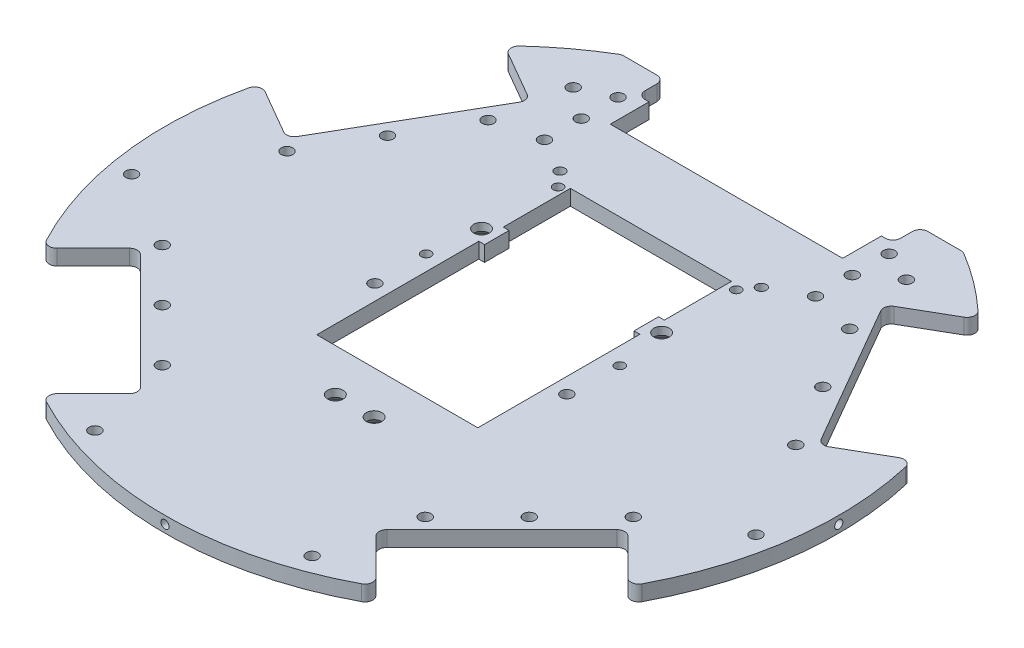
SolidWorks part; units mm, degrees
ref_plane "Front Plane" through (0, 0, 0) normal (0, 0, 1) x (1, 0, 0)
ref_plane "Top Plane" through (0, 0, 0) normal (0, 1, 0) x (1, 0, 0)
ref_plane "Right Plane" through (0, 0, 0) normal (1, 0, 0) x (0, 0, -1)
sketch "Sketch1" plane through (0, 0, 0) normal (0, 1, 0) x (1, 0, 0)
  line L0 (0, 75) -> (0, -70.0325) construction
  line L1 (0, 0) -> (57.1577, 33) construction
  line L2 (0, 0) -> (46.669, -46.669) construction
  line L3 (45.6577, 52.9186) -> (68.6577, 13.0814)
  line L4 (-44.0908, 75) -> (44.0908, 75) construction
  line L5 (62.9325, -30.4056) -> (30.4056, -62.9325)
  line L6 (45.6577, 52.9186) -> (61.1636, 61.8709)
  line L7 (68.6577, 13.0814) -> (84.1636, 22.0338)
  line L8 (30.4056, -62.9325) -> (43.0661, -75.593)
  line L9 (62.9325, -30.4056) -> (75.593, -43.0661)
  line L10 (-33, 69) -> (33, 69)
  line L11 (33, 69) -> (33, 75)
  line L12 (33, 75) -> (44.0908, 75)
  line L13 (0, 0) -> (-46.669, -46.669) construction
  line L14 (0, 0) -> (-57.1577, 33) construction
  line L15 (-33, 75) -> (-44.0908, 75)
  line L16 (-33, 69) -> (-33, 75)
  line L17 (-62.9325, -30.4056) -> (-75.593, -43.0661)
  line L18 (-30.4056, -62.9325) -> (-43.0661, -75.593)
  line L19 (-68.6577, 13.0814) -> (-84.1636, 22.0338)
  line L20 (-45.6577, 52.9186) -> (-61.1636, 61.8709)
  line L21 (-62.9325, -30.4056) -> (-30.4056, -62.9325)
  line L22 (-45.6577, 52.9186) -> (-68.6577, 13.0814)
  arc A0 (-43.0661, -75.593) -> (43.0661, -75.593) centre (0, 0) ccw
  arc A1 (61.1636, 61.8709) -> (44.0908, 75) centre (0, 0) ccw
  arc A2 (75.593, -43.0661) -> (84.1636, 22.0338) centre (0, 0) ccw
  arc A3 (-75.593, -43.0661) -> (-84.1636, 22.0338) centre (0, 0) cw
  arc A4 (-61.1636, 61.8709) -> (-44.0908, 75) centre (0, 0) cw
  point P27 (0, 69)
  dimension "D1" = 87
  dimension "D2" = 75
  dimension "D3" = 66
  dimension "D4" = 60
  dimension "D5" = 45
  dimension "D6" = 46
  dimension "D7" = 46
  dimension "D8" = 33
  dimension "D9" = 6
extrude "Boss-Extrude1" add sketch "Sketch1" along normal mid plane 4
fillet "Fillet1" radius 2 20 edges at (33, 0, -75) (-33, 0, -75) (44.0908, 0, -75) (68.6577, 0, -13.0814) (84.1636, 0, -22.0338) (45.6577, 0, -52.9186) (61.1636, 0, -61.8709) (62.9325, 0, 30.4056) (43.0661, 0, 75.593) (30.4056, 0, 62.9325) (75.593, 0, 43.0661) (-43.0661, 0, 75.593) (-30.4056, 0, 62.9325) (-75.593, 0, 43.0661) (-62.9325, 0, 30.4056) (-68.6577, 0, -13.0814) (-84.1636, 0, -22.0338) (-45.6577, 0, -52.9186) (-44.0908, 0, -75) (-61.1636, 0, -61.8709)
sketch "Sketch2" plane through (0, -2, 0) normal (0, -1, 0) x (-1, 0, 0)
  line L0 (46.6936, 43.1244) -> (65.6936, 10.2154) construction
  line L1 (60.8112, -26.8701) -> (33.9411, -53.7401) construction
  line L2 (46.6577, 51.1865) -> (67.6577, 14.8135) construction
  line L3 (61.5183, -31.8198) -> (31.8198, -61.5183) construction
  line L4 (70.3897, 14.0814) -> (81.8562, 20.7016) construction
  line L5 (73.7091, -41.1822) -> (64.3467, -31.8198) construction
  line L6 (35, 65) -> (35, 46) construction
  line L7 (26, 61) -> (26, 41) construction
  line L8 (35, 75) -> (43.5431, 75) construction
  line L9 (-33, 69) -> (33, 69) construction
  line L10 (-33, 69) -> (33, 69) construction
  line L11 (0, 69) -> (0, -87) construction
  line L12 (-26, 61) -> (-26, 41) construction
  line L13 (-35, 65) -> (-35, 46) construction
  line L14 (-60.8112, -26.8701) -> (-33.9411, -53.7401) construction
  line L15 (-46.6936, 43.1244) -> (-65.6936, 10.2154) construction
  arc A0 (-40.7037, -76.8909) -> (40.7037, -76.8909) centre (0, 0) ccw construction
  point P0 (46.6936, 43.1244)
  point P1 (56.1936, 26.6699)
  point P2 (65.6936, 10.2154)
  point P3 (60.8112, -26.8701)
  point P4 (47.3762, -40.3051)
  point P5 (33.9411, -53.7401)
  point P18 (35, 65)
  point P19 (35, 55.5)
  point P20 (35, 46)
  point P21 (26, 61)
  point P22 (26, 41)
  point P29 (0, 69)
  point P34 (0, 69)
  point P48 (-35, 55.5)
  point P49 (-47.3762, -40.3051)
  point P50 (-56.1936, 26.6699)
  dimension "D1" = 38
  dimension "D2" = 38
  dimension "D3" = 4
  dimension "D4" = 4
  dimension "D5" = 18
  dimension "D6" = 18
  dimension "D7" = 19
  dimension "D8" = 35
  dimension "10" = 10
  dimension "D9" = 20
  dimension "D10" = 8
  dimension "D11" = 26
hole_wizard "CSK for M3 SFHCS1" positions "3DSketch1" profile "Sketch3" countersink size "M3" standard "ANSI Metric"
sketch3d "3DSketch1"
  point P0 (46.6936, -2, -43.1244)
  point P3 (56.1936, -2, -26.6699)
  point P6 (65.6936, -2, -10.2154)
  point P9 (60.8112, -2, 26.8701)
  point P12 (47.3762, -2, 40.3051)
  point P15 (33.9411, -2, 53.7401)
  point P18 (-33.9411, -2, 53.7401)
  point P21 (-47.3762, -2, 40.3051)
  point P24 (-60.8112, -2, 26.8701)
  point P27 (-46.6936, -2, -43.1244)
  point P30 (-56.1936, -2, -26.6699)
  point P33 (-65.6936, -2, -10.2154)
  point P36 (-35, -2, -65)
  point P39 (-35, -2, -55.5)
  point P42 (-35, -2, -46)
  point P45 (35, -2, -46)
  point P48 (35, -2, -55.5)
  point P51 (35, -2, -65)
sketch "Sketch3" plane through (46.6936, -2, -43.1244) normal (1, 0, 0) x (0, 0, -1)
  line L0 (0, 0) -> (0, 10.4013)
  line L1 (0, 10.4013) -> (1.5, 9.5)
  line L2 (1.5, 9.5) -> (1.5, 1.3)
  line L3 (1.5, 1.3) -> (2.8, 0)
  line L5 (2.8, 0) -> (0, 0)
  line L6 (-1.5, 1.3) -> (-2.8, 0) construction
  line L10 (0, 10.4013) -> (-1.5, 9.5) construction
  line L11 (0, -6.35) -> (0, 107.95) construction
  dimension "Hole Dia." = 3
  dimension "Hole Depth" = 9.5
  dimension "Near C'Sink Dia." = 5.6
  dimension "Near C'Sink Angle" = 90
  dimension "Drill Angle" = 118
sketch "Sketch4" plane through (0, -2, 0) normal (0, -1, 0) x (1, 0, 0)
  line L0 (0, 0) -> (-43.0182, -61.4364) construction
  line L1 (0, 0) -> (-28.0457, 77.0548) construction
  line L2 (0, -69) -> (0, 87) construction
  line L3 (0, 0) -> (-80.6164, 15) construction
  line L4 (0, -69) -> (0, 87) construction
  line L5 (0, 0) -> (80.6164, 15) construction
  line L6 (0, 0) -> (28.0457, 77.0548) construction
  line L7 (0, 0) -> (43.0182, -61.4364) construction
  dimension "D1" = 75
  dimension "D2" = 35
  dimension "D3" = 82
  dimension "D4" = 20
  dimension "D5" = 82
  dimension "D6" = 15
hole_wizard "CSK for M3 SFHCS2" positions "3DSketch2" profile "Sketch5" countersink size "M3" standard "ANSI Metric"
sketch3d "3DSketch2"
  point P0 (43.0182, -2, -61.4364)
  point P3 (80.6164, -2, 15)
  point P6 (28.0457, -2, 77.0548)
  point P9 (-28.0457, -2, 77.0548)
  point P12 (-80.6164, -2, 15)
  point P15 (-43.0182, -2, -61.4364)
sketch "Sketch5" plane through (43.0182, -2, -61.4364) normal (1, 0, 0) x (0, 0, -1)
  line L0 (0, 0) -> (0, 10.4013)
  line L1 (0, 10.4013) -> (1.5, 9.5)
  line L2 (1.5, 9.5) -> (1.5, 1.3)
  line L3 (1.5, 1.3) -> (2.8, 0)
  line L5 (2.8, 0) -> (0, 0)
  line L6 (-1.5, 1.3) -> (-2.8, 0) construction
  line L10 (0, 10.4013) -> (-1.5, 9.5) construction
  line L11 (0, -6.35) -> (0, 107.95) construction
  dimension "Hole Dia." = 3
  dimension "Hole Depth" = 9.5
  dimension "Near C'Sink Dia." = 5.6
  dimension "Near C'Sink Angle" = 90
  dimension "Drill Angle" = 118
hole_wizard "CSK for M3 SFHCS3" positions "3DSketch3" profile "Sketch6" countersink size "M3" standard "ANSI Metric"
sketch3d "3DSketch3"
  point P0 (26, -2, -41)
  point P3 (26, -2, -61)
  point P6 (-26, -2, -41)
  point P9 (-26, -2, -61)
sketch "Sketch6" plane through (26, -2, -41) normal (1, 0, 0) x (0, 0, -1)
  line L0 (0, 0) -> (0, 10.2811)
  line L1 (0, 10.2811) -> (1.3, 9.5)
  line L2 (1.3, 9.5) -> (1.3, 1)
  line L3 (1.3, 1) -> (2.3, 0)
  line L5 (2.3, 0) -> (0, 0)
  line L6 (-1.3, 1) -> (-2.3, 0) construction
  line L10 (0, 10.2811) -> (-1.3, 9.5) construction
  line L11 (0, -6.35) -> (0, 107.95) construction
  dimension "Hole Dia." = 2.6
  dimension "Hole Depth" = 9.5
  dimension "Near C'Sink Dia." = 4.6
  dimension "Near C'Sink Angle" = 90
  dimension "Drill Angle" = 118
sketch "Sketch7" plane through (0, 0, 0) normal (0, 1, 0) x (1, 0, 0)
  arc A0 (-84.8058, 19.4159) -> (-76.8909, -40.7037) centre (0, 0) ccw construction
  arc A1 (76.8909, -40.7037) -> (84.8058, 19.4159) centre (0, 0) ccw construction
  arc A2 (-40.7037, -76.8909) -> (40.7037, -76.8909) centre (0, 0) ccw construction
  arc A3 (59.2176, 63.736) -> (44.5676, 74.7176) centre (0, 0) ccw construction
  arc A4 (-44.5676, 74.7176) -> (-59.2176, 63.736) centre (0, 0) ccw construction
  point P0 (-86.2557, -11.3558)
  point P1 (86.2557, -11.3558)
  point P5 (0, -87)
  point P9 (52.1823, 69.6133)
  point P13 (-52.1823, 69.6133)
ref_plane "Plane1" through (87, 0, 0) normal (1, 0, 0) x (0, 0, -1)
sketch "Sketch9" plane through (87, 0, 0) normal (1, 0, 0) x (0, 0, -1)
  circle A0 centre (0, 0) radius 1.05
  dimension "D1" = 2.1
ref_plane "Plane2" through (0, 0, 87) normal (0, 0, 1) x (1, 0, 0)
sketch "Sketch10" plane through (0, 0, 87) normal (0, 0, 1) x (1, 0, 0)
  circle A0 centre (0, 0) radius 1.05
  dimension "D1" = 2.1
ref_plane "Plane3" through (52.1823, 0, -69.6133) normal (0.5998, 0, -0.8002) x (-0.8002, 0, -0.5998)
sketch "Sketch11" plane through (52.1823, 0, -69.6133) normal (0.5998, 0, -0.8002) x (-0.8002, 0, -0.5998)
  circle A0 centre (0, 0) radius 1.05
  dimension "D1" = 2.1
sketch "Sketch12" plane through (0, 2, 0) normal (0, 1, 0) x (1, 0, 0)
  line L0 (-23.25, 18) -> (23.25, 18) construction
  line L1 (24.78, -8) -> (-24.78, -8) construction
  line L2 (-5, -38) -> (5, -38) construction
  line L3 (33, 69) -> (-33, 69) construction
  line L4 (-35, 75) -> (-43.5431, 75) construction
  point P0 (-23.25, 18)
  point P1 (23.25, 18)
  point P2 (-5, -38)
  point P3 (5, -38)
  point P4 (-24.78, -8)
  point P5 (24.78, -8)
  point P14 (0, 18)
  point P16 (0, -8)
  point P17 (0, -38)
  dimension "D1" = 51
  dimension "D2" = 83
  dimension "D3" = 56
  dimension "D4" = 49.56
  dimension "D5" = 10
  dimension "D6" = 46.5
sketch "Sketch14" plane through (0, -2, 0) normal (0, -1, 0) x (1, 0, 0)
  point P0 (23.25, -18)
  point P1 (-23.25, -18)
  point P3 (-24.78, 8)
  point P5 (24.78, 8)
  point P7 (5, 38)
  point P9 (-5, 38)
hole_wizard "CSK for M4 SFHCS3" positions "3DSketch7" profile "Sketch16" countersink size "M4" standard "ANSI Metric"
sketch3d "3DSketch7"
  point P0 (23.25, -2, -18)
  point P3 (-23.25, -2, -18)
  point P6 (-5, -2, 38)
  point P9 (5, -2, 38)
sketch "Sketch16" plane through (23.25, -2, -18) normal (1, 0, 0) x (0, 0, -1)
  line L0 (0, 0) -> (0, 10.7017)
  line L1 (0, 10.7017) -> (2, 9.5)
  line L2 (2, 9.5) -> (2, 2)
  line L3 (2, 2) -> (4, 0)
  line L5 (4, 0) -> (0, 0)
  line L6 (-2, 2) -> (-4, 0) construction
  line L10 (0, 10.7017) -> (-2, 9.5) construction
  line L11 (0, -6.35) -> (0, 107.95) construction
  dimension "Hole Dia." = 4
  dimension "Hole Depth" = 9.5
  dimension "Near C'Sink Dia." = 8
  dimension "Near C'Sink Angle" = 90
  dimension "Drill Angle" = 118
hole_wizard "CSK for M3 SFHCS4" positions "3DSketch8" profile "Sketch17" countersink size "M3" standard "ANSI Metric"
sketch3d "3DSketch8"
  point P0 (24.78, -2, 8)
  point P3 (-24.78, -2, 8)
sketch "Sketch17" plane through (24.78, -2, 8) normal (1, 0, 0) x (0, 0, -1)
  line L0 (0, 0) -> (0, 10.4013)
  line L1 (0, 10.4013) -> (1.5, 9.5)
  line L2 (1.5, 9.5) -> (1.5, 1.3)
  line L3 (1.5, 1.3) -> (2.8, 0)
  line L5 (2.8, 0) -> (0, 0)
  line L6 (-1.5, 1.3) -> (-2.8, 0) construction
  line L10 (0, 10.4013) -> (-1.5, 9.5) construction
  line L11 (0, -6.35) -> (0, 107.95) construction
  dimension "Hole Dia." = 3
  dimension "Hole Depth" = 9.5
  dimension "Near C'Sink Dia." = 5.6
  dimension "Near C'Sink Angle" = 90
  dimension "Drill Angle" = 118
extrude "Cut-Extrude1" cut sketch "Sketch9" against normal blind 8
extrude "Cut-Extrude2" cut sketch "Sketch10" against normal blind 8
extrude "Cut-Extrude3" cut sketch "Sketch11" against normal blind 8
mirror "Mirror1" about plane through (0, 0, 0) normal (1, 0, 0) of "Cut-Extrude3", "Cut-Extrude2", "Cut-Extrude1"
sketch "Sketch18" plane through (0, 2, 0) normal (0, 1, 0) x (1, 0, 0)
  line L0 (-44.8999, 78) -> (44.8999, 78) construction
  line L1 (-35, 75) -> (-43.5431, 75) construction
  circle A0 centre (0, 0) radius 90 construction
  dimension "D1" = 180
  dimension "D2" = 3
hole_wizard "M2.5x0.45 Tapped Hole1" positions "3DSketch9" profile "Sketch19" tap size "M2.5x0.45" standard "ANSI Metric"
sketch3d "3DSketch9"
  line L0 (-35, 2, -75) -> (-43.5431, 2, -75) construction
  line L1 (43.5431, 2, -75) -> (35, 2, -75) construction
  line L2 (-35, -2, -75) -> (-43.5431, -2, -75) construction
  point P0 (-39.2715, 0, -75)
  point P2 (39.4456, 0, -75)
  point P11 (-39.2715, -2, -75)
  dimension "D1" = 2
  dimension "D2" = 2
sketch "Sketch19" plane through (-39.2715, 0, -75) normal (1, 0, 0) x (0, 1, 0)
  line L0 (0, 0) -> (0, 6.9659)
  line L1 (0, 6.9659) -> (1.025, 6.35)
  line L2 (1.025, 6.35) -> (1.025, 0)
  line L5 (1.025, 0) -> (0, 0)
  line L10 (0, 6.9659) -> (-1.025, 6.35) construction
  line L11 (0, -6.35) -> (0, 107.95) construction
  dimension "Tap Drill Dia." = 2.05
  dimension "Tap Drill Depth" = 6.35
  dimension "Drill Angle" = 118
sketch "Sketch21" plane through (0, 2, 0) normal (0, 1, 0) x (1, 0, 0)
  line L17 (43.5431, 75) -> (35, 75)
  line L18 (33, 73) -> (33, 69)
  line L19 (33, 69) -> (-33, 69)
  line L20 (-33, 69) -> (-33, 73)
  line L21 (-35, 75) -> (-43.5431, 75)
  line L22 (-58.8562, 60.5388) -> (-47.3897, 53.9186)
  line L23 (-46.6577, 51.1865) -> (-67.6577, 14.8135)
  line L24 (-70.3897, 14.0814) -> (-81.8562, 20.7016)
  line L25 (-73.7091, -41.1822) -> (-64.3467, -31.8198)
  line L26 (-61.5183, -31.8198) -> (-31.8198, -61.5183)
  line L27 (-31.8198, -64.3467) -> (-41.1822, -73.7091)
  line L28 (41.1822, -73.7091) -> (31.8198, -64.3467)
  line L29 (31.8198, -61.5183) -> (61.5183, -31.8198)
  line L30 (64.3467, -31.8198) -> (73.7091, -41.1822)
  line L31 (81.8562, 20.7016) -> (70.3897, 14.0814)
  line L32 (67.6577, 14.8135) -> (46.6577, 51.1865)
  line L33 (47.3897, 53.9186) -> (58.8562, 60.5388)
  line L34 (43.5431, 75) -> (35, 75)
  line L35 (33, 73) -> (33, 69)
  line L36 (33, 69) -> (-33, 69)
  line L37 (-33, 69) -> (-33, 73)
  line L38 (-35, 75) -> (-43.5431, 75)
  line L39 (-58.8562, 60.5388) -> (-47.3897, 53.9186)
  line L40 (-46.6577, 51.1865) -> (-67.6577, 14.8135)
  line L41 (-70.3897, 14.0814) -> (-81.8562, 20.7016)
  line L42 (-73.7091, -41.1822) -> (-64.3467, -31.8198)
  line L43 (-61.5183, -31.8198) -> (-31.8198, -61.5183)
  line L44 (-31.8198, -64.3467) -> (-41.1822, -73.7091)
  line L45 (41.1822, -73.7091) -> (31.8198, -64.3467)
  line L46 (31.8198, -61.5183) -> (61.5183, -31.8198)
  line L47 (64.3467, -31.8198) -> (73.7091, -41.1822)
  line L48 (81.8562, 20.7016) -> (70.3897, 14.0814)
  line L49 (67.6577, 14.8135) -> (46.6577, 51.1865)
  line L50 (47.3897, 53.9186) -> (58.8562, 60.5388)
  circle A1 centre (25.24, 5.2127) radius 1.25
  circle A2 centre (25.24, 5.2127) radius 1.25
  circle A3 centre (-24.76, 5.2127) radius 1.25
  circle A4 centre (-24.76, 5.2127) radius 1.25
  circle A5 centre (-22.685, 37.2127) radius 1.25
  circle A6 centre (-22.685, 37.2127) radius 1.25
  circle A7 centre (23.315, 37.2127) radius 1.25
  circle A8 centre (23.315, 37.2127) radius 1.25
  arc A27 (35, 75) -> (33, 73) centre (35, 73) ccw
  arc A30 (-33, 73) -> (-35, 75) centre (-35, 73) ccw
  arc A31 (-43.5431, 75) -> (-44.5676, 74.7176) centre (-43.5431, 73) ccw
  arc A32 (-44.5676, 74.7176) -> (-59.2176, 63.736) centre (0, 0) ccw
  arc A33 (-59.2176, 63.736) -> (-58.8562, 60.5388) centre (-57.8562, 62.2708) ccw
  arc A34 (-46.6577, 51.1865) -> (-47.3897, 53.9186) centre (-48.3897, 52.1865) ccw
  arc A35 (-70.3897, 14.0814) -> (-67.6577, 14.8135) centre (-69.3897, 15.8135) ccw
  arc A36 (-81.8562, 20.7016) -> (-84.8058, 19.4159) centre (-82.8562, 18.9696) ccw
  arc A37 (-84.8058, 19.4159) -> (-76.8909, -40.7037) centre (0, 0) ccw
  arc A38 (-76.8909, -40.7037) -> (-73.7091, -41.1822) centre (-75.1233, -39.768) ccw
  arc A39 (-61.5183, -31.8198) -> (-64.3467, -31.8198) centre (-62.9325, -33.234) ccw
  arc A40 (-31.8198, -64.3467) -> (-31.8198, -61.5183) centre (-33.234, -62.9325) ccw
  arc A41 (-41.1822, -73.7091) -> (-40.7037, -76.8909) centre (-39.768, -75.1233) ccw
  arc A42 (-40.7037, -76.8909) -> (40.7037, -76.8909) centre (0, 0) ccw
  arc A43 (40.7037, -76.8909) -> (41.1822, -73.7091) centre (39.768, -75.1233) ccw
  arc A44 (31.8198, -61.5183) -> (31.8198, -64.3467) centre (33.234, -62.9325) ccw
  arc A45 (64.3467, -31.8198) -> (61.5183, -31.8198) centre (62.9325, -33.234) ccw
  arc A46 (73.7091, -41.1822) -> (76.8909, -40.7037) centre (75.1233, -39.768) ccw
  arc A47 (76.8909, -40.7037) -> (84.8058, 19.4159) centre (0, 0) ccw
  arc A48 (84.8058, 19.4159) -> (81.8562, 20.7016) centre (82.8562, 18.9696) ccw
  arc A49 (67.6577, 14.8135) -> (70.3897, 14.0814) centre (69.3897, 15.8135) ccw
  arc A50 (47.3897, 53.9186) -> (46.6577, 51.1865) centre (48.3897, 52.1865) ccw
  arc A51 (58.8562, 60.5388) -> (59.2176, 63.736) centre (57.8562, 62.2708) ccw
  arc A52 (59.2176, 63.736) -> (44.5676, 74.7176) centre (0, 0) ccw
  arc A53 (44.5676, 74.7176) -> (43.5431, 75) centre (43.5431, 73) ccw
  arc A54 (35, 75) -> (33, 73) centre (35, 73) ccw
  arc A57 (-33, 73) -> (-35, 75) centre (-35, 73) ccw
  arc A58 (-43.5431, 75) -> (-44.5676, 74.7176) centre (-43.5431, 73) ccw
  arc A59 (-44.5676, 74.7176) -> (-59.2176, 63.736) centre (0, 0) ccw
  arc A60 (-59.2176, 63.736) -> (-58.8562, 60.5388) centre (-57.8562, 62.2708) ccw
  arc A61 (-46.6577, 51.1865) -> (-47.3897, 53.9186) centre (-48.3897, 52.1865) ccw
  arc A62 (-70.3897, 14.0814) -> (-67.6577, 14.8135) centre (-69.3897, 15.8135) ccw
  arc A63 (-81.8562, 20.7016) -> (-84.8058, 19.4159) centre (-82.8562, 18.9696) ccw
  arc A64 (-84.8058, 19.4159) -> (-76.8909, -40.7037) centre (0, 0) ccw
  arc A65 (-76.8909, -40.7037) -> (-73.7091, -41.1822) centre (-75.1233, -39.768) ccw
  arc A66 (-61.5183, -31.8198) -> (-64.3467, -31.8198) centre (-62.9325, -33.234) ccw
  arc A67 (-31.8198, -64.3467) -> (-31.8198, -61.5183) centre (-33.234, -62.9325) ccw
  arc A68 (-41.1822, -73.7091) -> (-40.7037, -76.8909) centre (-39.768, -75.1233) ccw
  arc A69 (-40.7037, -76.8909) -> (40.7037, -76.8909) centre (0, 0) ccw
  arc A70 (40.7037, -76.8909) -> (41.1822, -73.7091) centre (39.768, -75.1233) ccw
  arc A71 (31.8198, -61.5183) -> (31.8198, -64.3467) centre (33.234, -62.9325) ccw
  arc A72 (64.3467, -31.8198) -> (61.5183, -31.8198) centre (62.9325, -33.234) ccw
  arc A73 (73.7091, -41.1822) -> (76.8909, -40.7037) centre (75.1233, -39.768) ccw
  arc A74 (76.8909, -40.7037) -> (84.8058, 19.4159) centre (0, 0) ccw
  arc A75 (84.8058, 19.4159) -> (81.8562, 20.7016) centre (82.8562, 18.9696) ccw
  arc A76 (67.6577, 14.8135) -> (70.3897, 14.0814) centre (69.3897, 15.8135) ccw
  arc A77 (47.3897, 53.9186) -> (46.6577, 51.1865) centre (48.3897, 52.1865) ccw
  arc A78 (58.8562, 60.5388) -> (59.2176, 63.736) centre (57.8562, 62.2708) ccw
  arc A79 (59.2176, 63.736) -> (44.5676, 74.7176) centre (0, 0) ccw
  arc A80 (44.5676, 74.7176) -> (43.5431, 75) centre (43.5431, 73) ccw
  dimension "D1" = 0
  dimension "D2" = 0
  dimension "D3" = 0
  dimension "D4" = 0
  dimension "D5" = 0
extrude "Cut-Extrude4" cut sketch "Sketch21" against normal up to next contours A2 | A8 | A4 | A6
sketch "Sketch23" plane through (0, 0, -69) normal (0, 0, -1) x (-1, 0, 0)
  line L1 (33, -2) -> (-33, -2)
  line L2 (33, -2) -> (33, 2)
  line L3 (33, 2) -> (-33, 2)
  line L4 (-33, -2) -> (-33, 2)
extrude "Cut-Extrude6" cut sketch "Sketch23" against normal blind 1
fillet "Fillet2" radius 2 2 edges at (33, 0, -68) (-33, 0, -68)
sketch "Sketch24" plane through (0, -2, 0) normal (0, -1, 0) x (1, 0, 0)
  line L0 (31, -68) -> (-31, -68) construction
  line L1 (-20.8, 27) -> (20.8, 27)
  line L2 (-20.8, 27) -> (-20.8, -14.8381)
  line L3 (-20.8, -38.5) -> (20.8, -38.5)
  line L4 (20.8, 27) -> (20.8, -14.8381)
  line L5 (-20.8, -14.8381) -> (-19.3, -14.8381)
  line L6 (-19.3, -14.8381) -> (-19.3, -21.1619)
  line L7 (-19.3, -21.1619) -> (-20.8, -21.1619)
  line L8 (-20.8, -21.1619) -> (-20.8, -38.5)
  line L9 (20.8, -14.8381) -> (19.3, -14.8381)
  line L10 (19.3, -14.8381) -> (19.3, -21.1619)
  line L11 (19.3, -21.1619) -> (20.8, -21.1619)
  line L12 (20.8, -21.1619) -> (20.8, -38.5)
  circle A0 centre (-23.25, -18) radius 4 construction
  circle A1 centre (23.25, -18) radius 4 construction
  point P6 (0, -68)
  point P7 (0, 27)
  point P13 (0, 0)
  point P21 (0, 0)
  dimension "D1" = 29.5
  dimension "D2" = 41.6
  dimension "D3" = 65.5
  dimension "D4" = 1.5
  dimension "D5" = 1.5
extrude "Cut-Extrude9" cut sketch "Sketch24" against normal blind 10 contours L2 L5 L6 L7 L8 L3 L12 L11 L10 L9 L4 L1
sketch "Sketch25" plane through (0, 0, -68) normal (0, 0, -1) x (-1, 0, 0)
  line L0 (31, 2) -> (-31, 2) construction
  line L1 (-30, 2) -> (30, 2)
  line L2 (-30, 2) -> (-30, -2)
  line L3 (-30, -2) -> (30, -2)
  line L4 (30, 2) -> (30, -2)
  line L5 (-31, -2) -> (31, -2) construction
  line L6 (-31, 2) -> (-31, -2) construction
  line L7 (31, -2) -> (31, 2) construction
  dimension "D1" = 1
  dimension "D2" = 1
extrude "Cut-Extrude10" cut sketch "Sketch25" against normal blind 10
